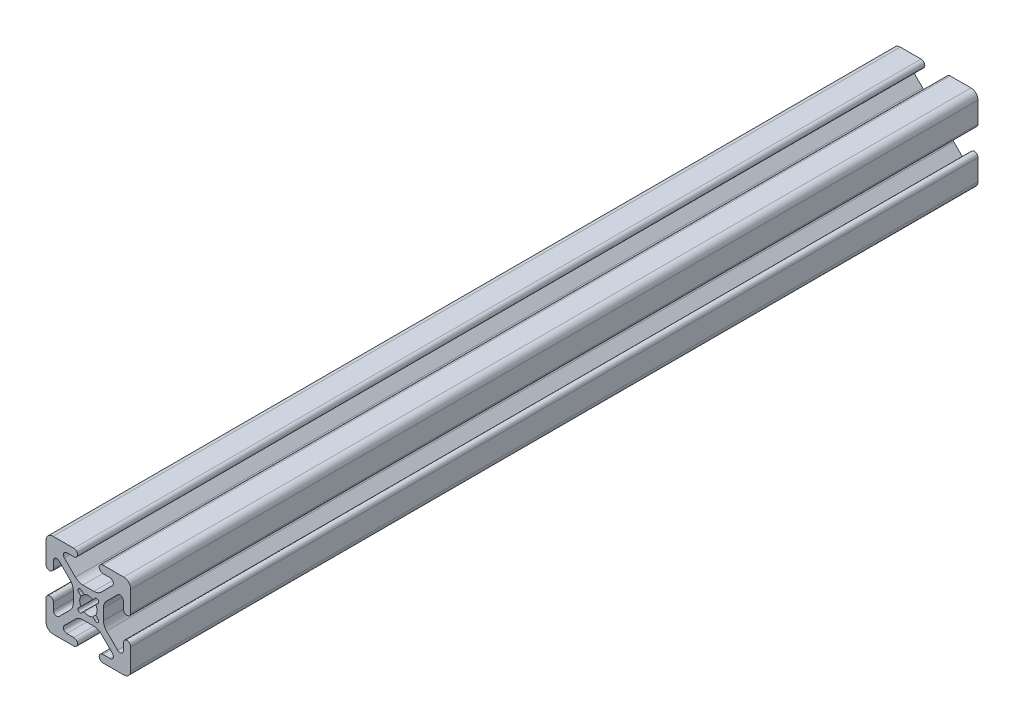
SolidWorks part; units mm, degrees
material "6105-T5 Aluminum"
ref_plane "Front Plane" through (0, 0, 0) normal (0, 0, 1) x (1, 0, 0)
ref_plane "Top Plane" through (0, 0, 0) normal (0, 1, 0) x (1, 0, 0)
ref_plane "Right Plane" through (0, 0, 0) normal (1, 0, 0) x (0, 0, -1)
sketch "Sketch1" plane through (0, 0, 0) normal (0, 0, 1) x (1, 0, 0)
  line L0 (-2.8605, -1.9692) -> (-2.2319, -1.3405)
  line L1 (-2.2319, 1.3405) -> (-2.8605, 1.9692)
  line L2 (-1.9692, 2.8605) -> (-1.3405, 2.2319)
  line L3 (1.3405, 2.2319) -> (1.9692, 2.8605)
  line L4 (2.8605, 1.9692) -> (2.2319, 1.3405)
  line L5 (2.2319, -1.3405) -> (2.8605, -1.9692)
  line L6 (1.9692, -2.8605) -> (1.3405, -2.2319)
  line L7 (-1.3405, -2.2319) -> (-1.9692, -2.8605)
  line L8 (-3.8846, 5.4471) -> (-7.1933, 8.7558)
  line L9 (1.6396, 4.5172) -> (-1.6396, 4.5172)
  line L10 (7.1933, 8.7558) -> (3.8846, 5.4471)
  line L11 (12.7, -10.5918) -> (12.7, -4.3561)
  line L12 (5.4471, 3.8846) -> (8.7558, 7.1933)
  line L13 (4.5172, -1.6396) -> (4.5172, 1.6396)
  line L14 (8.7558, -7.1933) -> (5.4471, -3.8846)
  line L15 (-10.5918, -12.7) -> (-4.3561, -12.7)
  line L16 (3.8846, -5.4471) -> (7.1933, -8.7558)
  line L17 (-1.6396, -4.5172) -> (1.6396, -4.5172)
  line L18 (-7.1933, -8.7558) -> (-3.8846, -5.4471)
  line L19 (-12.7, 10.5918) -> (-12.7, 4.3561)
  line L20 (-5.4471, -3.8846) -> (-8.7558, -7.1933)
  line L21 (-4.5172, 1.6396) -> (-4.5172, -1.6396)
  line L22 (-8.7558, 7.1933) -> (-5.4471, 3.8846)
  line L23 (-10.5918, 12.7) -> (-4.3561, 12.7)
  line L24 (-6.4749, 10.4902) -> (-4.3561, 10.4902)
  line L25 (-10.4902, 6.4749) -> (-10.4902, 4.3561)
  line L26 (-6.4749, -10.4902) -> (-4.3561, -10.4902)
  line L27 (10.4902, -6.4749) -> (10.4902, -4.3561)
  line L28 (4.3561, 12.7) -> (10.5918, 12.7)
  line L29 (4.3561, 10.4902) -> (6.4749, 10.4902)
  line L30 (-10.4902, -4.3561) -> (-10.4902, -6.4749)
  line L31 (-12.7, -4.3561) -> (-12.7, -10.5918)
  line L32 (4.3561, -10.4902) -> (6.4749, -10.4902)
  line L33 (4.3561, -12.7) -> (10.5918, -12.7)
  line L34 (12.7, 4.3561) -> (12.7, 10.5918)
  line L35 (10.4902, 4.3561) -> (10.4902, 6.4749)
  arc A0 (-2.8605, -1.9692) -> (-1.9692, -2.8605) centre (-2.4696, -2.4696) ccw
  arc A1 (-2.2319, 1.3405) -> (-2.2319, -1.3405) centre (0, 0) ccw
  arc A2 (-1.9692, 2.8605) -> (-2.8605, 1.9692) centre (-2.4696, 2.4696) ccw
  arc A3 (1.3405, 2.2319) -> (-1.3405, 2.2319) centre (0, 0) ccw
  arc A4 (2.8605, 1.9692) -> (1.9692, 2.8605) centre (2.4696, 2.4696) ccw
  arc A5 (2.2319, -1.3405) -> (2.2319, 1.3405) centre (0, 0) ccw
  arc A6 (1.9692, -2.8605) -> (2.8605, -1.9692) centre (2.4696, -2.4696) ccw
  arc A7 (-1.3405, -2.2319) -> (1.3405, -2.2319) centre (0, 0) ccw
  arc A8 (-3.8846, 5.4471) -> (-1.6396, 4.5172) centre (-1.6396, 7.6922) ccw
  arc A9 (1.6396, 4.5172) -> (3.8846, 5.4471) centre (1.6396, 7.6922) ccw
  arc A10 (5.4471, 3.8846) -> (4.5172, 1.6396) centre (7.6922, 1.6396) ccw
  arc A11 (4.5172, -1.6396) -> (5.4471, -3.8846) centre (7.6922, -1.6396) ccw
  arc A12 (3.8846, -5.4471) -> (1.6396, -4.5172) centre (1.6396, -7.6922) ccw
  arc A13 (-1.6396, -4.5172) -> (-3.8846, -5.4471) centre (-1.6396, -7.6922) ccw
  arc A14 (-5.4471, -3.8846) -> (-4.5172, -1.6396) centre (-7.6922, -1.6396) ccw
  arc A15 (-4.5172, 1.6396) -> (-5.4471, 3.8846) centre (-7.6922, 1.6396) ccw
  arc A16 (-12.7, -10.5918) -> (-10.5918, -12.7) centre (-10.5918, -10.5918) ccw
  arc A17 (10.5918, -12.7) -> (12.7, -10.5918) centre (10.5918, -10.5918) ccw
  arc A18 (12.7, 10.5918) -> (10.5918, 12.7) centre (10.5918, 10.5918) ccw
  arc A19 (-10.5918, 12.7) -> (-12.7, 10.5918) centre (-10.5918, 10.5918) ccw
  arc A20 (-8.7558, 7.1933) -> (-10.4902, 6.4749) centre (-9.4742, 6.4749) ccw
  arc A21 (-6.4749, 10.4902) -> (-7.1933, 8.7558) centre (-6.4749, 9.4742) ccw
  arc A22 (7.1933, 8.7558) -> (6.4749, 10.4902) centre (6.4749, 9.4742) ccw
  arc A23 (10.4902, 6.4749) -> (8.7558, 7.1933) centre (9.4742, 6.4749) ccw
  arc A24 (8.7558, -7.1933) -> (10.4902, -6.4749) centre (9.4742, -6.4749) ccw
  arc A25 (6.4749, -10.4902) -> (7.1933, -8.7558) centre (6.4749, -9.4742) ccw
  arc A26 (-7.1933, -8.7558) -> (-6.4749, -10.4902) centre (-6.4749, -9.4742) ccw
  arc A27 (-10.4902, -6.4749) -> (-8.7558, -7.1933) centre (-9.4742, -6.4749) ccw
  arc A28 (-4.3561, 10.4902) -> (-4.3561, 12.7) centre (-4.3561, 11.5951) ccw
  arc A29 (4.3561, 12.7) -> (4.3561, 10.4902) centre (4.3561, 11.5951) ccw
  arc A30 (-12.7, 4.3561) -> (-10.4902, 4.3561) centre (-11.5951, 4.3561) ccw
  arc A31 (-10.4902, -4.3561) -> (-12.7, -4.3561) centre (-11.5951, -4.3561) ccw
  arc A32 (-4.3561, -12.7) -> (-4.3561, -10.4902) centre (-4.3561, -11.5951) ccw
  arc A33 (4.3561, -10.4902) -> (4.3561, -12.7) centre (4.3561, -11.5951) ccw
  arc A34 (12.7, -4.3561) -> (10.4902, -4.3561) centre (11.5951, -4.3561) ccw
  arc A35 (10.4902, 4.3561) -> (12.7, 4.3561) centre (11.5951, 4.3561) ccw
extrude "Extrude1" add sketch "Sketch1" against normal blind 254
